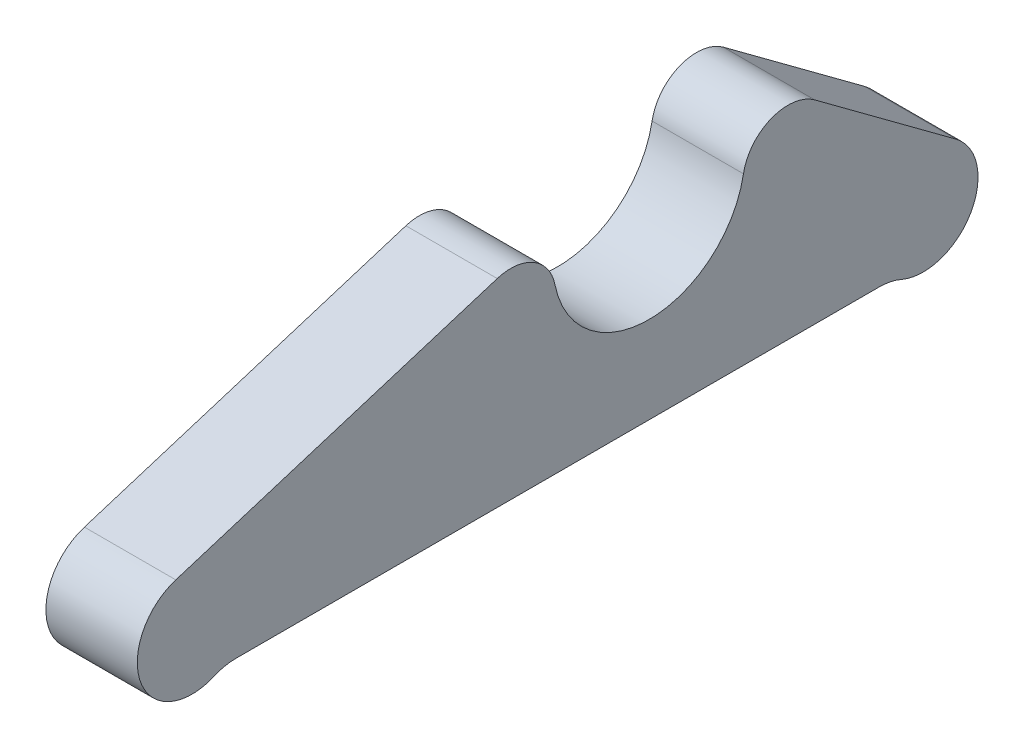
SolidWorks part; units mm, degrees
ref_plane "Front Plane" through (0, 0, 0) normal (0, 0, 1) x (1, 0, 0)
ref_plane "Top Plane" through (0, 0, 0) normal (0, 1, 0) x (1, 0, 0)
ref_plane "Right Plane" through (0, 0, 0) normal (1, 0, 0) x (0, 0, -1)
sketch "Sketch1" plane through (0, 0, 0) normal (1, 0, 0) x (0, 0, -1)
  line L0 (-50, -15) -> (30, -15) construction
  line L1 (30, -15) -> (0, 0) construction
  line L2 (0, 0) -> (-50, -15) construction
  line L3 (0, 0) -> (0, -15) construction
  line L4 (-45.2042, -20) -> (25.2042, -20)
  line L5 (-51.7862, -9.272) -> (-16.6095, 1.6971)
  line L6 (33.5706, -10.1781) -> (18.1357, 1.2512)
  line L7 (-56.5742, -21) -> (44.6607, -21) construction
  circle A0 centre (0, 0) radius 8.6142 construction
  arc A1 (-51.7862, -9.272) -> (-47.6021, -20.5) centre (-50, -15) ccw
  arc A2 (33.5706, -10.1781) -> (27.6021, -20.5) centre (30, -15) cw
  arc A3 (25.2042, -20) -> (27.6021, -20.5) centre (25.2042, -26) cw
  arc A4 (-45.2042, -20) -> (-47.6021, -20.5) centre (-45.2042, -26) ccw
  arc A5 (-10.2931, -2.0532) -> (10.3317, -1.8491) centre (0, 0) ccw
  arc A6 (-16.6095, 1.6971) -> (-10.2931, -2.0532) centre (-15.1386, -3.0198) cw
  arc A7 (18.1357, 1.2512) -> (10.3317, -1.8491) centre (15.1954, -2.7196) ccw
  point P9 (-56.5729, -21.4717)
  point P15 (18.1357, 1.2512)
  dimension "D5" = 6
  dimension "D1" = 15
  dimension "D2" = 80
  dimension "D3" = 30
  dimension "D4" = 1
extrude "Boss-Extrude1" add sketch "Sketch1" along normal blind 10
